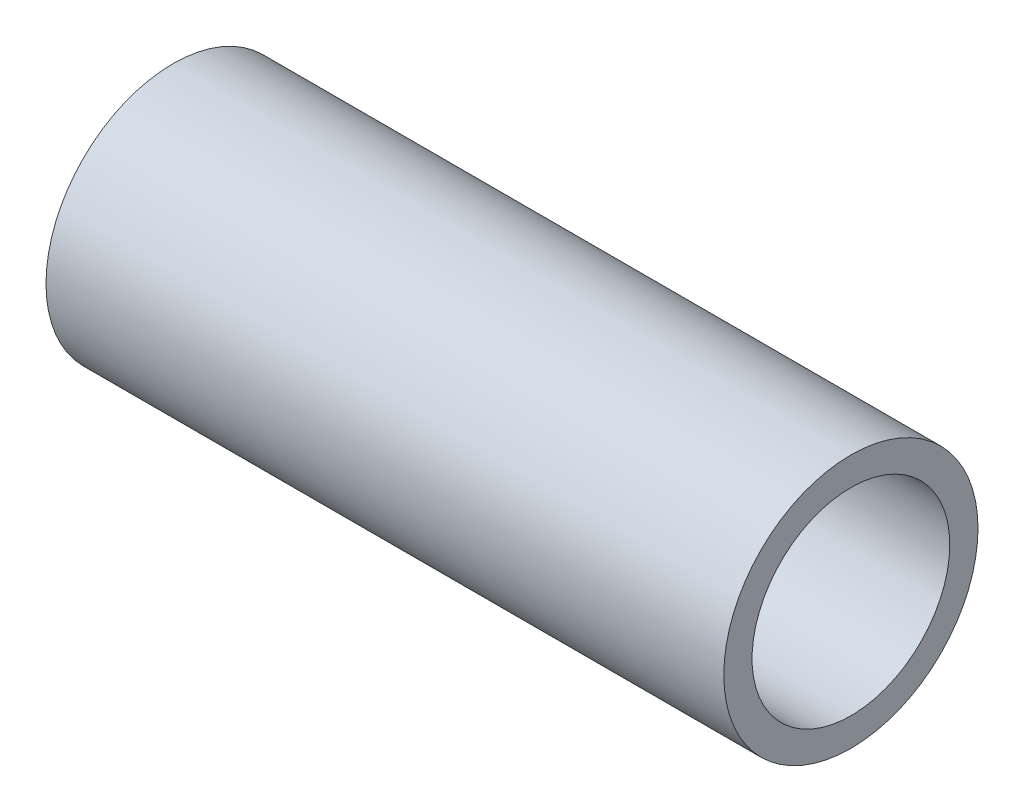
SolidWorks part; units mm, degrees
ref_plane "Ebene vorne" through (0, 0, 0) normal (0, 0, 1) x (1, 0, 0)
ref_plane "Ebene oben" through (0, 0, 0) normal (0, 1, 0) x (1, 0, 0)
ref_plane "Ebene rechts" through (0, 0, 0) normal (1, 0, 0) x (0, 0, -1)
sketch "Sketch1" plane through (0, 0, 0) normal (1, 0, 0) x (0, 0, -1)
  circle A0 centre (0, 0) radius 9
  circle A1 centre (0, 0) radius 7
  dimension "D1" = 18
  dimension "D2" = 14
extrude "Boss-Extrude1" add sketch "Sketch1" along normal mid plane 48
